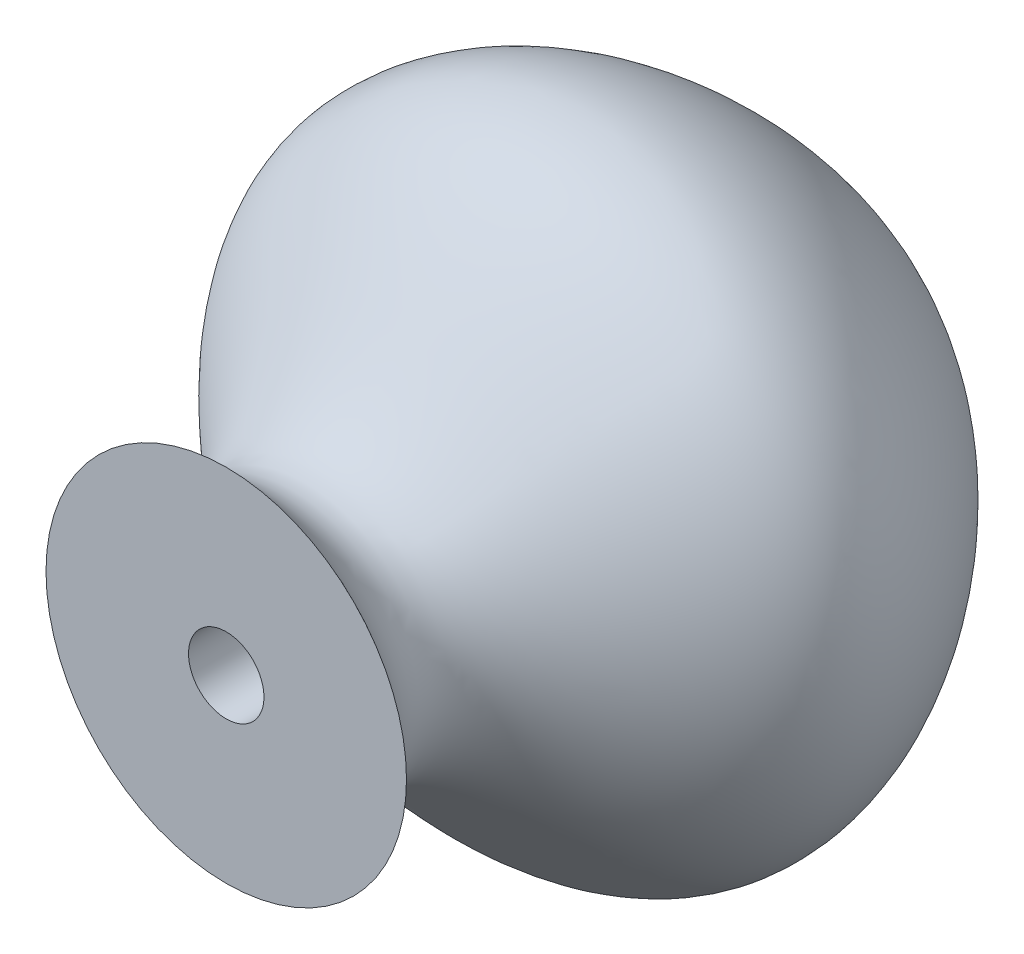
SolidWorks part; units mm, degrees
ref_plane "前视基准面" through (0, 0, 0) normal (0, 0, 1) x (1, 0, 0)
ref_plane "上视基准面" through (0, 0, 0) normal (0, 1, 0) x (1, 0, 0)
ref_plane "右视基准面" through (0, 0, 0) normal (1, 0, 0) x (0, 0, -1)
other "Configuration Table"
sketch "草图1" plane through (0, 0, 0) normal (0, 1, 0) x (1, 0, 0)
  line L1 (0, 16.5) -> (0, -16.5)
  line L2 (0, -16.5) -> (9.5543, -16.5)
  arc A1 (11.0751, 12.2308) -> (10.8149, 12.4615) centre (0, 0) ccw
  spline S0 degree 3 poles (0, 16.5) (7.1587, 18.1464) (22.205, 3.9497) (10.6151, -7.39) (3.8667, -12.6641) (9.5543, -16.5) knots 0 0 0 0 0.549519 0.720751 1 1 1 1
revolve "旋转7" add sketch "草图1" angle 360 about L1
sketch "草图2" plane through (0, 0, 16.5) normal (0, 0, 1) x (1, 0, 0)
  circle A0 centre (0, 0) radius 2
  dimension "D1" = 4
extrude "切除-拉伸1" cut sketch "草图2" against normal blind 5
